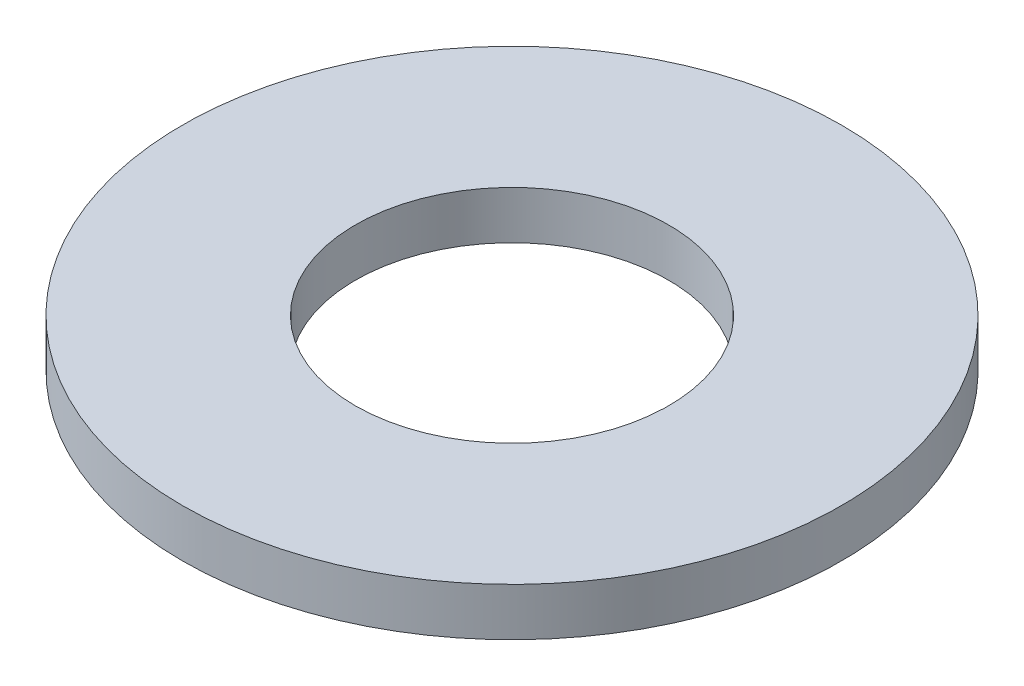
SolidWorks part; units mm, degrees
ref_plane "Front Plane" through (0, 0, 0) normal (0, 0, 1) x (1, 0, 0)
ref_plane "Top Plane" through (0, 0, 0) normal (0, 1, 0) x (1, 0, 0)
ref_plane "Right Plane" through (0, 0, 0) normal (1, 0, 0) x (0, 0, -1)
sketch "Sketch1" plane through (0, 0, 0) normal (0, 1, 0) x (1, 0, 0)
  circle A0 centre (0, 0) radius 5.5
  circle A1 centre (0, 0) radius 2.615
  dimension "D1" = 5.23
  dimension "D2" = 11
extrude "Boss-Extrude1" add sketch "Sketch1" along normal blind 0.8
